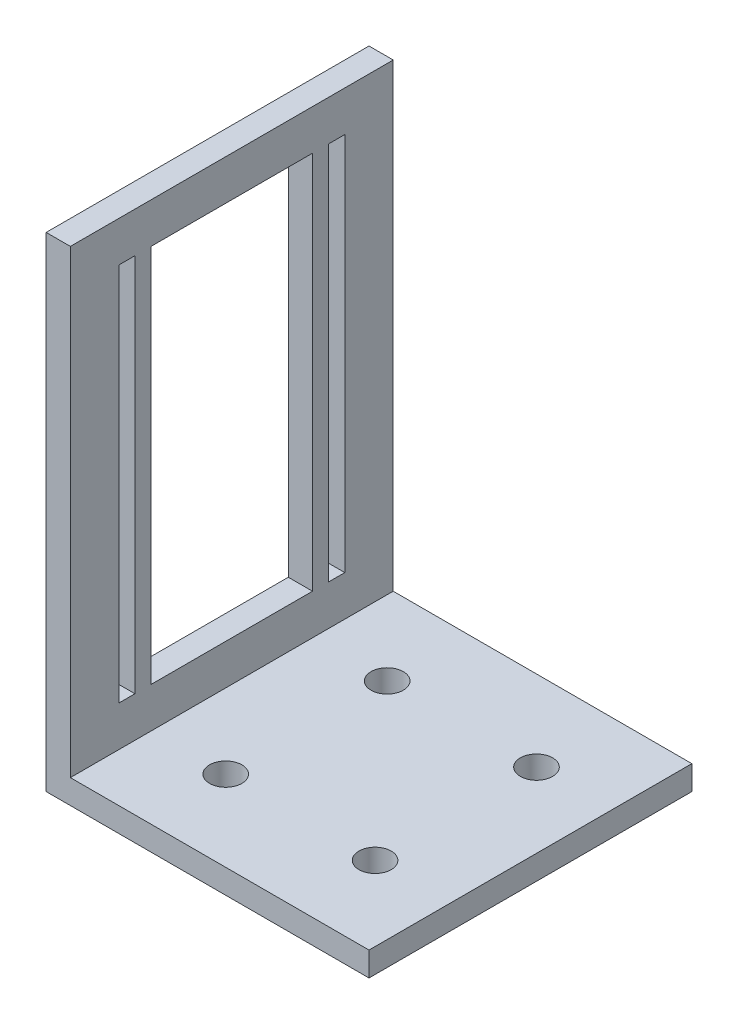
SolidWorks part; units mm, degrees
ref_plane "Front Plane" through (0, 0, 0) normal (0, 0, 1) x (1, 0, 0)
ref_plane "Top Plane" through (0, 0, 0) normal (0, 1, 0) x (1, 0, 0)
ref_plane "Right Plane" through (0, 0, 0) normal (1, 0, 0) x (0, 0, -1)
sketch "Sketch1" plane through (0, 0, 0) normal (0, 0, 1) x (1, 0, 0)
  line L0 (0, 0) -> (-40, 0)
  line L1 (-40, 0) -> (-40, 60)
  line L2 (0, 3) -> (-37, 3)
  line L3 (-37, 3) -> (-37, 60)
  line L4 (-37, 60) -> (-40, 60)
  line L5 (0, 0) -> (0, 3)
  dimension "D1" = 40
  dimension "D2" = 60
  dimension "D3" = 3
  dimension "D4" = 3
extrude "Boss-Extrude1" add sketch "Sketch1" along normal blind 40
sketch "Sketch2" plane through (0, 3, 0) normal (0, 1, 0) x (1, 0, 0)
  line L0 (-37, -20) -> (0, -20) construction
  line L1 (-37, -40) -> (-37, 0) construction
  line L2 (0, -40) -> (0, 0) construction
  line L3 (-18.5, 0) -> (-18.5, -40) construction
  line L4 (0, 0) -> (-37, 0) construction
  line L5 (0, -40) -> (-37, -40) construction
  line L6 (-18.5, -20) -> (0, -40) construction
  line L7 (0, -20) -> (-18.5, -40) construction
  circle A1 centre (-9.25, -30) radius 2
  circle A2 centre (-27.75, -30) radius 2
  circle A3 centre (-27.75, -10) radius 2
  circle A4 centre (-9.25, -10) radius 2
  dimension "D1" = 4
extrude "Cut-Extrude1" cut sketch "Sketch2" against normal blind 40
sketch "Sketch3" plane through (-40, 0, 0) normal (-1, 0, 0) x (0, 0, 1)
  line L0 (20, 60) -> (20, 0) construction
  line L1 (40, 60) -> (0, 60) construction
  line L2 (40, 0) -> (0, 0) construction
  line L3 (32, 55) -> (32, 8)
  line L4 (34, 55) -> (34, 8)
  line L5 (34, 55) -> (32, 55)
  line L6 (34, 8) -> (32, 8)
  line L7 (6, 8) -> (8, 8)
  line L8 (6, 55) -> (8, 55)
  line L9 (6, 55) -> (6, 8)
  line L10 (8, 55) -> (8, 8)
  line L11 (30, 55) -> (30, 8)
  line L12 (10, 55) -> (10, 8)
  line L13 (10, 55) -> (30, 55)
  line L14 (30, 8) -> (10, 8)
  line L15 (33, 55) -> (33, 8) construction
  dimension "D1" = 5
  dimension "D2" = 12
  dimension "D3" = 8
  dimension "D5" = 2
  dimension "D4" = 2
extrude "Cut-Extrude2" cut sketch "Sketch3" against normal through all
